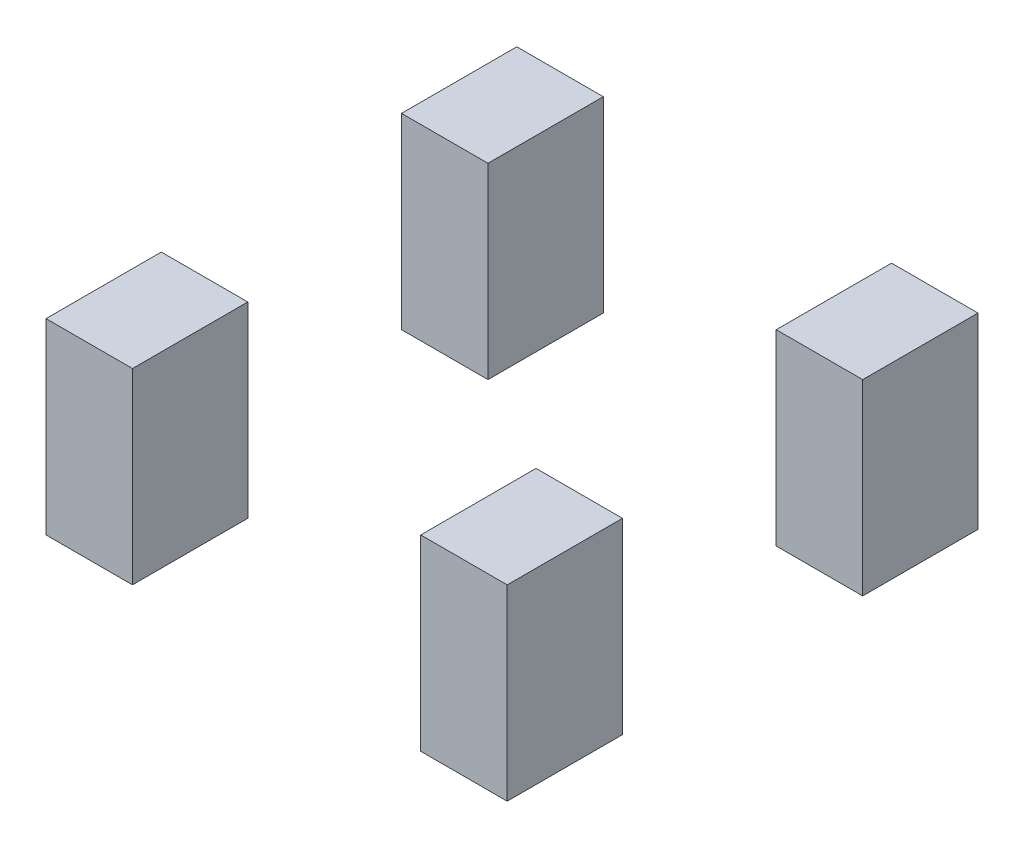
SolidWorks part; units mm, degrees
ref_plane "Front Plane" through (0, 0, 0) normal (0, 0, 1) x (1, 0, 0)
ref_plane "Top Plane" through (0, 0, 0) normal (0, 1, 0) x (1, 0, 0)
ref_plane "Right Plane" through (0, 0, 0) normal (1, 0, 0) x (0, 0, -1)
sketch "Sketch1" plane through (0, 0, 0) normal (0, 1, 0) x (1, 0, 0)
  line L0 (-1714.8144, -5320.4941) -> (-1624.8144, -5320.4941)
  line L5 (-1714.8144, -5320.4941) -> (-1714.8144, -5440.4941)
  line L6 (-1714.8144, -5440.4941) -> (-1624.8144, -5440.4941)
  line L7 (-1624.8144, -5320.4941) -> (-1624.8144, -5440.4941)
  line L8 (-1474.8144, -4813.9083) -> (-1474.8144, -5577.0798) construction
  line L17 (-923.5635, -5195.4941) -> (-2026.0654, -5195.4941) construction
  line L18 (-1624.8144, -5070.4941) -> (-1624.8144, -4950.4941)
  line L19 (-1714.8144, -4950.4941) -> (-1624.8144, -4950.4941)
  line L20 (-1714.8144, -5070.4941) -> (-1714.8144, -4950.4941)
  line L21 (-1714.8144, -5070.4941) -> (-1624.8144, -5070.4941)
  line L22 (-1234.8144, -5070.4941) -> (-1324.8144, -5070.4941)
  line L23 (-1234.8144, -5070.4941) -> (-1234.8144, -4950.4941)
  line L24 (-1234.8144, -4950.4941) -> (-1324.8144, -4950.4941)
  line L25 (-1324.8144, -5070.4941) -> (-1324.8144, -4950.4941)
  line L26 (-1324.8144, -5320.4941) -> (-1324.8144, -5440.4941)
  line L27 (-1234.8144, -5440.4941) -> (-1324.8144, -5440.4941)
  line L28 (-1234.8144, -5320.4941) -> (-1234.8144, -5440.4941)
  line L29 (-1234.8144, -5320.4941) -> (-1324.8144, -5320.4941)
  point P15 (-1474.8144, -5195.4941)
  dimension "D1" = 125
  dimension "D3" = 90
  dimension "D4" = 120
  dimension "D7" = 150
extrude "Boss-Extrude1" add sketch "Sketch1" along normal blind 195
